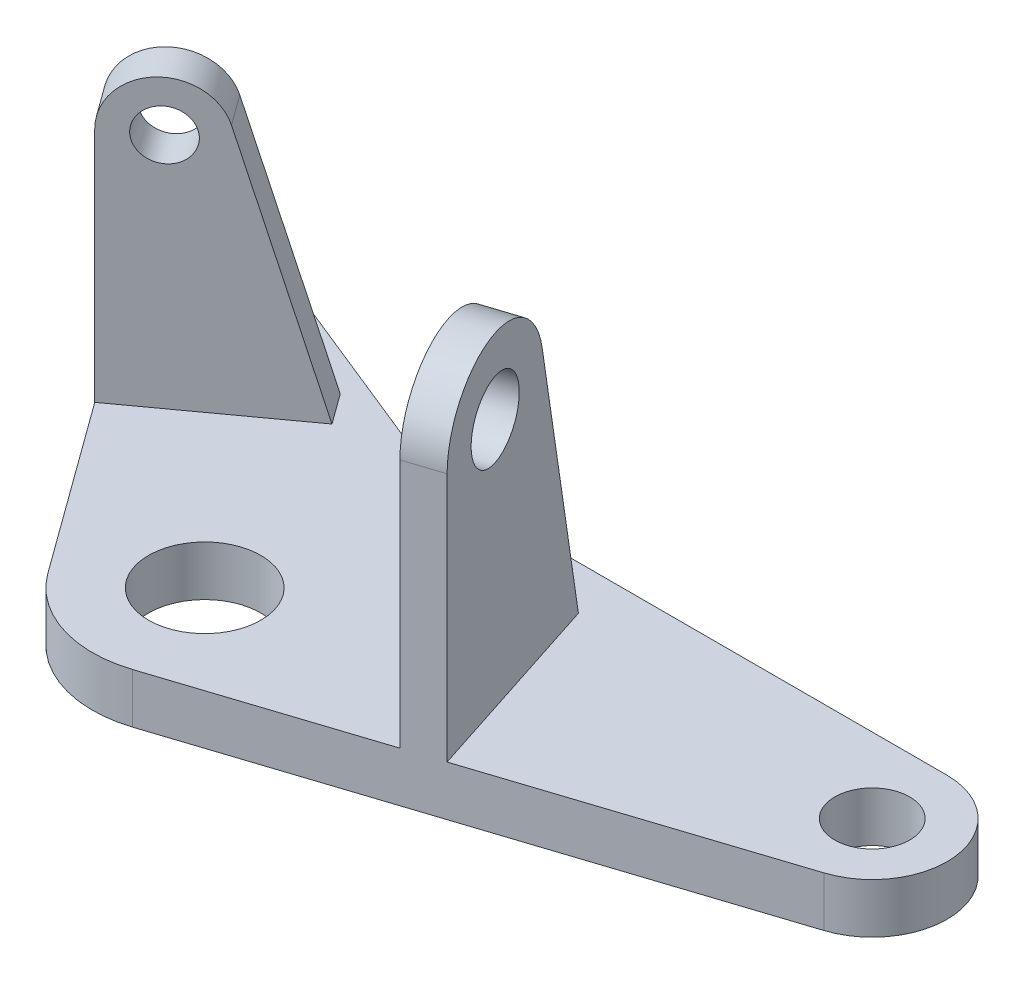
SolidWorks part; units mm, degrees
material "6061-T4 (SS)"
ref_plane "Front Plane" through (0, 0, 0) normal (0, 0, 1) x (1, 0, 0)
ref_plane "Top Plane" through (0, 0, 0) normal (0, 1, 0) x (1, 0, 0)
ref_plane "Right Plane" through (0, 0, 0) normal (1, 0, 0) x (0, 0, -1)
sketch "Sketch1" plane through (0, 0, 0) normal (0, 1, 0) x (1, 0, 0)
  line L0 (82, 0) -> (0, 0)
  line L1 (0, 0) -> (-45.0031, 18.1825)
  line L2 (-54.4721, 6.0627) -> (-18.0618, -44.0518)
  line L3 (2.0628, -50.5907) -> (85.7082, -23.4127)
  line L4 (-58.0127, -27.3434) -> (-21.607, -0.893) construction
  line L5 (44.2048, -60.5559) -> (30.299, -17.7583) construction
  circle A0 centre (-48, 10.765) radius 4
  circle A1 centre (82, -12) radius 6
  circle A2 centre (-3.4995, -33.4717) radius 9
  arc A3 (85.7082, -23.4127) -> (82, 0) centre (82, -12) ccw
  arc A4 (-18.0618, -44.0518) -> (2.0628, -50.5907) centre (-3.4995, -33.4717) ccw
  arc A5 (-45.0031, 18.1825) -> (-54.4721, 6.0627) centre (-48, 10.765) ccw
  point P15 (32.7712, -28.1795)
  point P16 (28.4399, -21.7446)
  point P19 (42.6517, -65.4842)
  point P20 (41.4067, -61.6525)
  dimension "D1" = 24
  dimension "D2" = 12
  dimension "D5" = 16
  dimension "D6" = 8
  dimension "D8" = 18
  dimension "D9" = 36
  dimension "D3" = 82
  dimension "D4" = 48
  dimension "D7" = 22
  dimension "D10" = 18
  dimension "D11" = 54
  dimension "D12" = 37
  dimension "D13" = 45
  dimension "D14" = 22.5
  dimension "D15" = 22.5
  dimension "D16" = 45
  dimension "D17" = 37
extrude "Boss-Extrude1" add sketch "Sketch1" along normal blind 8
ref_plane "Plane2" through (-7.0404, 0, -9.6902) normal (0.5878, 0, 0.809) x (0.809, 0, -0.5878)
ref_plane "Plane3" through (22.1867, 0, -7.2089) normal (0.9511, 0, -0.309) x (-0.309, 0, -0.9511)
sketch "Sketch2" plane through (-7.0404, 0, -9.6902) normal (0.5878, 0, 0.809) x (0.809, 0, -0.5878)
  line L0 (-40.5053, 8) -> (-40.5053, 46)
  line L1 (-24.8152, 48.2051) -> (-13.2866, 8)
  line L2 (-28.0676, 8) -> (55.5778, 8) construction
  line L3 (-13.2866, 8) -> (-40.5053, 8)
  line L4 (-40.5053, 0) -> (-28.0676, 0) construction
  arc A0 (-24.8152, 48.2051) -> (-40.5053, 46) centre (-32.5053, 46) ccw
  circle A1 centre (-32.5053, 46) radius 4
  point P10 (0, 0)
  point P11 (-35.5196, 36.5192)
  dimension "D2" = 8
  dimension "D3" = 16
  dimension "D1" = 46
  dimension "D4" = 16
extrude "Boss-Extrude2" add sketch "Sketch2" along normal mid plane 6
sketch "Sketch3" plane through (22.1867, 0, -7.2089) normal (0.9511, 0, -0.309) x (-0.309, 0, -0.9511)
  line L0 (-48.7521, 8) -> (-48.7521, 48)
  line L1 (-25.0143, 50.4949) -> (-15.9817, 8)
  line L2 (-25.3394, 8) -> (0, 8) construction
  line L3 (-48.7521, 8) -> (-15.9817, 8)
  line L4 (-48.7521, 0) -> (-25.3394, 0) construction
  arc A0 (-48.7521, 48) -> (-25.0143, 50.4949) centre (-36.7521, 48) cw
  circle A1 centre (-36.7521, 48) radius 6
  dimension "D1" = 12
  dimension "D2" = 12
  dimension "D3" = 48
  dimension "D4" = 12
extrude "Boss-Extrude3" add sketch "Sketch3" along normal mid plane 6
